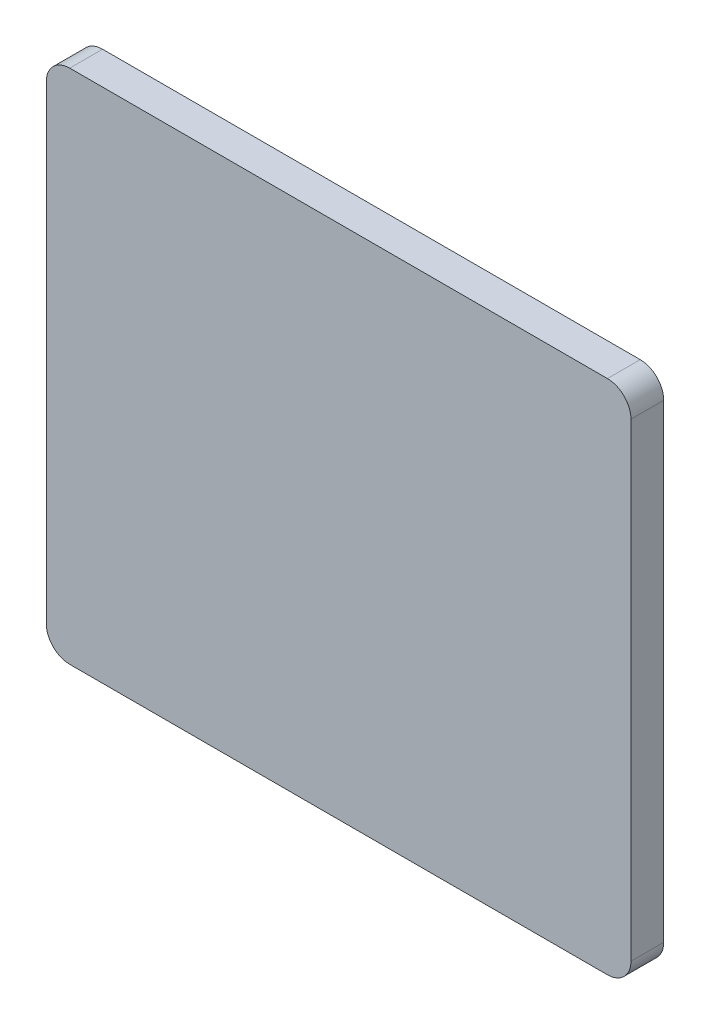
SolidWorks part; units mm, degrees
ref_plane "Front Plane" through (0, 0, 0) normal (0, 0, 1) x (1, 0, 0)
ref_plane "Top Plane" through (0, 0, 0) normal (0, 1, 0) x (1, 0, 0)
ref_plane "Right Plane" through (0, 0, 0) normal (1, 0, 0) x (0, 0, -1)
sketch "Sketch2" plane through (0, 0, 0) normal (0, 0, 1) x (1, 0, 0)
  line L4 (-97.5, 69.7) -> (-97.5, -16.2)
  line L5 (-95.2, -18.5) -> (3.2, -18.5)
  line L6 (5.5, -16.2) -> (5.5, 69.7)
  line L7 (3.2, 72) -> (-95.2, 72)
  line L8 (-97.5, 69.7) -> (-97.5, -16.2)
  line L9 (-95.2, -18.5) -> (3.2, -18.5)
  line L10 (5.5, -16.2) -> (5.5, 69.7)
  line L11 (3.2, 72) -> (-95.2, 72)
  arc A4 (-97.5, -16.2) -> (-95.2, -18.5) centre (-95.2, -16.2) ccw
  arc A5 (3.2, -18.5) -> (5.5, -16.2) centre (3.2, -16.2) ccw
  arc A6 (5.5, 69.7) -> (3.2, 72) centre (3.2, 69.7) ccw
  arc A7 (-95.2, 72) -> (-97.5, 69.7) centre (-95.2, 69.7) ccw
  arc A8 (-97.5, -16.2) -> (-95.2, -18.5) centre (-95.2, -16.2) ccw
  arc A9 (3.2, -18.5) -> (5.5, -16.2) centre (3.2, -16.2) ccw
  arc A10 (5.5, 69.7) -> (3.2, 72) centre (3.2, 69.7) ccw
  arc A11 (-95.2, 72) -> (-97.5, 69.7) centre (-95.2, 69.7) ccw
  dimension "D1" = 0
sketch "Sketch3" plane through (0, 0, 0) normal (0, 0, 1) x (1, 0, 0)
  line L4 (-97.5, 69.7) -> (-97.5, -16.2)
  line L5 (-95.2, -18.5) -> (3.2, -18.5)
  line L6 (5.5, -16.2) -> (5.5, 69.7)
  line L7 (3.2, 72) -> (-95.2, 72)
  line L8 (-97.5, 69.7) -> (-97.5, -16.2)
  line L9 (-95.2, -18.5) -> (3.2, -18.5)
  line L10 (5.5, -16.2) -> (5.5, 69.7)
  line L11 (3.2, 72) -> (-95.2, 72)
  arc A4 (-97.5, -16.2) -> (-95.2, -18.5) centre (-95.2, -16.2) ccw
  arc A5 (3.2, -18.5) -> (5.5, -16.2) centre (3.2, -16.2) ccw
  arc A6 (5.5, 69.7) -> (3.2, 72) centre (3.2, 69.7) ccw
  arc A7 (-95.2, 72) -> (-97.5, 69.7) centre (-95.2, 69.7) ccw
  arc A8 (-97.5, -16.2) -> (-95.2, -18.5) centre (-95.2, -16.2) ccw
  arc A9 (3.2, -18.5) -> (5.5, -16.2) centre (3.2, -16.2) ccw
  arc A10 (5.5, 69.7) -> (3.2, 72) centre (3.2, 69.7) ccw
  arc A11 (-95.2, 72) -> (-97.5, 69.7) centre (-95.2, 69.7) ccw
  dimension "D1" = 0
extrude "Boss-Extrude3" add sketch "Sketch3" along normal blind 5
sketch "Sketch4" plane through (0, 0, 5) normal (0, 0, 1) x (1, 0, 0)
  line L8 (-99.5, 69.7) -> (-99.5, -16.2)
  line L9 (-95.2, -20.5) -> (3.2, -20.5)
  line L10 (7.5, -16.2) -> (7.5, 69.7)
  line L11 (3.2, 74) -> (-95.2, 74)
  line L12 (-99.5, 69.7) -> (-99.5, -16.2)
  line L13 (-95.2, -20.5) -> (3.2, -20.5)
  line L14 (7.5, -16.2) -> (7.5, 69.7)
  line L15 (3.2, 74) -> (-95.2, 74)
  arc A8 (-95.2, 74) -> (-99.5, 69.7) centre (-95.2, 69.7) ccw
  arc A9 (-99.5, -16.2) -> (-95.2, -20.5) centre (-95.2, -16.2) ccw
  arc A10 (3.2, -20.5) -> (7.5, -16.2) centre (3.2, -16.2) ccw
  arc A11 (7.5, 69.7) -> (3.2, 74) centre (3.2, 69.7) ccw
  arc A12 (-95.2, 74) -> (-99.5, 69.7) centre (-95.2, 69.7) ccw
  arc A13 (-99.5, -16.2) -> (-95.2, -20.5) centre (-95.2, -16.2) ccw
  arc A14 (3.2, -20.5) -> (7.5, -16.2) centre (3.2, -16.2) ccw
  arc A15 (7.5, 69.7) -> (3.2, 74) centre (3.2, 69.7) ccw
  dimension "D1" = 2
extrude "Boss-Extrude5" add sketch "Sketch4" against normal blind 6
